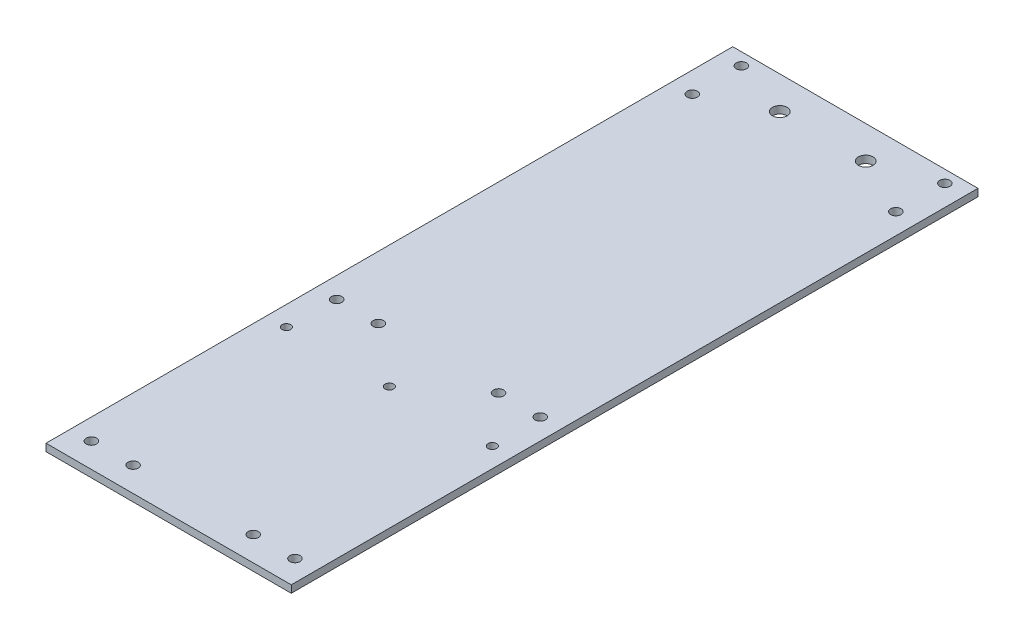
SolidWorks part; units mm, degrees
ref_plane "Front Plane" through (0, 0, 0) normal (0, 0, 1) x (1, 0, 0)
ref_plane "Top Plane" through (0, 0, 0) normal (0, 1, 0) x (1, 0, 0)
ref_plane "Right Plane" through (0, 0, 0) normal (1, 0, 0) x (0, 0, -1)
sketch "Sketch1" plane through (0, 0, 0) normal (0, 1, 0) x (1, 0, 0)
  line L1 (-50, 60) -> (50, 60)
  line L2 (-50, 60) -> (-50, -60)
  line L3 (-50, -60) -> (50, -60)
  line L4 (50, 60) -> (50, -60)
  line L5 (-50, 60) -> (50, -60) construction
  line L6 (-50, -60) -> (50, 60) construction
  line L7 (71.831, 0) -> (-33.8294, 0) construction
  line L8 (0, 117.1606) -> (0, -73.5833) construction
  circle A0 centre (41.5, 50) radius 2.1
  circle A1 centre (41.5, -50) radius 2.1
  circle A2 centre (-41.5, -50) radius 2.1
  circle A3 centre (-41.5, 50) radius 2.1
  circle A4 centre (-42, 30) radius 1.75
  circle A5 centre (0, 30) radius 1.75
  circle A6 centre (42, 30) radius 1.75
  point P0 (0, 0)
  dimension "D3" = 8.5
  dimension "D4" = 10
  dimension "D5" = 4.2
  dimension "D8" = 3.5
  dimension "D1" = 100
  dimension "D2" = 120
  dimension "D6" = 60
  dimension "D7" = 50
extrude "Boss-Extrude1" add sketch "Sketch1" along normal blind 3
sketch "Sketch2" plane through (0, 0, 0) normal (0, -1, 0) x (1, 0, 0)
  circle A0 centre (-24.5, -50) radius 2.1
  circle A1 centre (24.5, -50) radius 2.1
  circle A2 centre (24.5, 50) radius 2.1
  circle A3 centre (-24.5, 50) radius 2.1
extrude "Cut-Extrude1" cut sketch "Sketch2" against normal blind 10
sketch "Sketch3" plane through (0, 0, -60) normal (0, 0, -1) x (-1, 0, 0)
  line L1 (50, 0) -> (-50, 0)
  line L2 (50, 0) -> (50, 3)
  line L3 (50, 3) -> (-50, 3)
  line L4 (-50, 0) -> (-50, 3)
extrude "Boss-Extrude2" add sketch "Sketch3" along normal blind 160
sketch "Sketch4" plane through (0, 0, 0) normal (0, -1, 0) x (1, 0, 0)
  circle A0 centre (17.5, -206.7) radius 3
  circle A1 centre (-17.5, -206.7) radius 3
  circle A2 centre (-41.5, -215) radius 2.1
  circle A3 centre (-41.5, -195) radius 2.1
  circle A4 centre (41.5, -195) radius 2.1
  circle A5 centre (41.5, -215) radius 2.1
  dimension "D1" = 4.2
  dimension "D2" = 6
extrude "Cut-Extrude2" cut sketch "Sketch4" against normal blind 160
